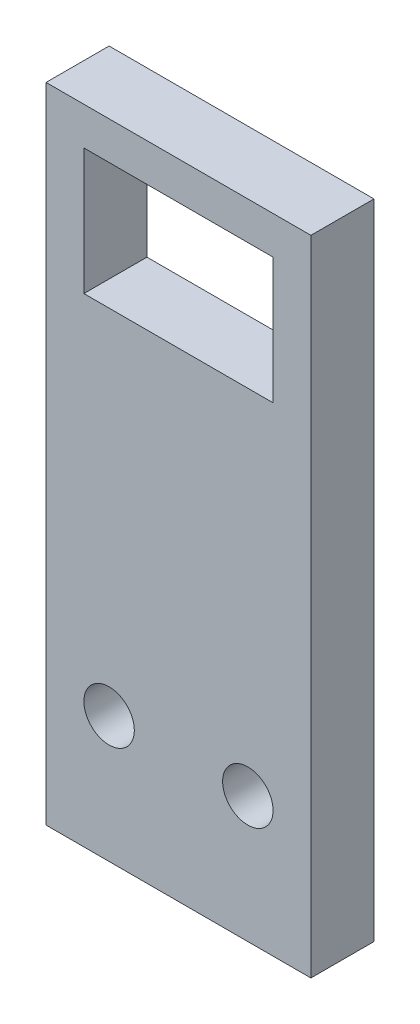
SolidWorks part; units mm, degrees
ref_plane "Front Plane" through (0, 0, 0) normal (0, 0, 1) x (1, 0, 0)
ref_plane "Top Plane" through (0, 0, 0) normal (0, 1, 0) x (1, 0, 0)
ref_plane "Right Plane" through (0, 0, 0) normal (1, 0, 0) x (0, 0, -1)
sketch "Sketch1" plane through (0, 0, 0) normal (0, 0, 1) x (1, 0, 0)
  line L1 (0, 0) -> (21, 0)
  line L2 (0, 0) -> (0, 51)
  line L3 (0, 51) -> (21, 51)
  line L4 (21, 0) -> (21, 51)
  line L5 (3, 48) -> (18, 48)
  line L6 (3, 48) -> (3, 38)
  line L7 (3, 38) -> (18, 38)
  line L8 (18, 48) -> (18, 38)
  circle A0 centre (5, 10) radius 2
  circle A1 centre (16, 10) radius 2
  dimension "D6" = 4
  dimension "D9" = 5
  dimension "D1" = 10
  dimension "D2" = 15
  dimension "D3" = 21
  dimension "D4" = 3
  dimension "D5" = 3
  dimension "D7" = 10
  dimension "D8" = 10
  dimension "D10" = 5
  dimension "D11" = 38
extrude "Boss-Extrude1" add sketch "Sketch1" along normal blind 5
